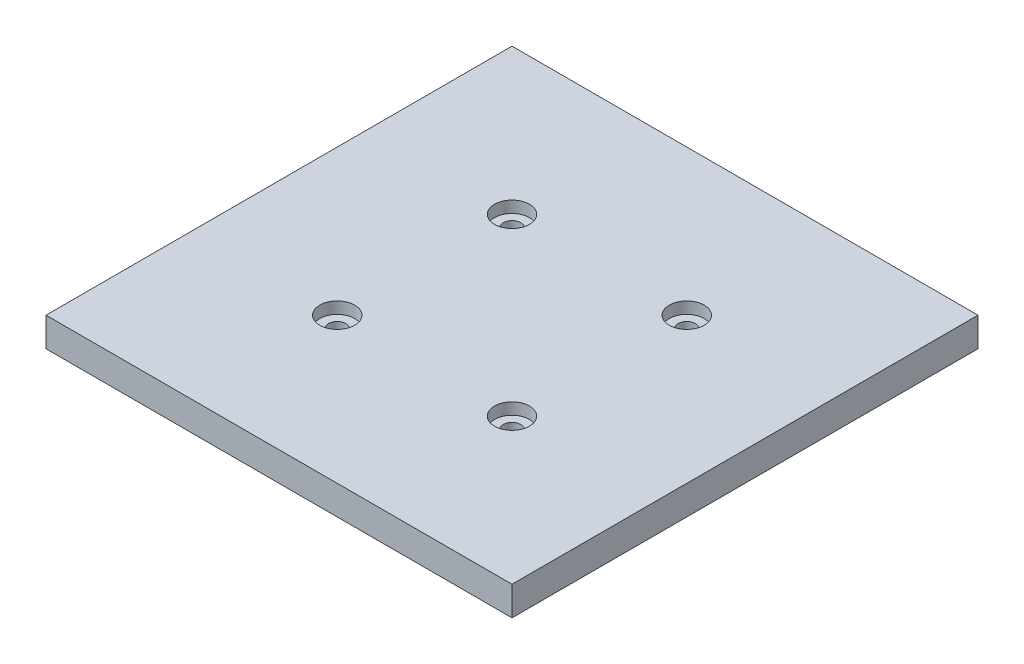
SolidWorks part; units mm, degrees
material "ABS"
ref_plane "Plan de face" through (0, 0, 0) normal (0, 0, 1) x (1, 0, 0)
ref_plane "Plan de dessus" through (0, 0, 0) normal (0, 1, 0) x (1, 0, 0)
ref_plane "Plan de droite" through (0, 0, 0) normal (1, 0, 0) x (0, 0, -1)
sketch "Esquisse1" plane through (0, 0, 0) normal (0, 1, 0) x (1, 0, 0)
  line L0 (0, 0) -> (0, 40) construction
  line L1 (-40, 40) -> (40, 40)
  line L2 (-40, 40) -> (-40, -40)
  line L3 (-40, -40) -> (40, -40)
  line L4 (40, 40) -> (40, -40)
  line L5 (0, 0) -> (40, 0) construction
  circle A0 centre (-15, 15) radius 1.5
  circle A1 centre (15, 15) radius 1.5
  circle A2 centre (-15, -15) radius 1.5
  circle A3 centre (15, -15) radius 1.5
  dimension "D4" = 3
  dimension "D1" = 80
  dimension "D2" = 15
  dimension "D3" = 15
extrude "Extrusion1" add sketch "Esquisse1" along normal blind 5
sketch "Esquisse2" plane through (0, 5, 0) normal (0, 1, 0) x (1, 0, 0)
  line L0 (0, 0) -> (0, 40) construction
  line L1 (40, 40) -> (-40, 40) construction
  line L2 (0, 0) -> (40, 0) construction
  line L3 (40, -40) -> (40, 40) construction
  circle A0 centre (-15, 15) radius 3
  circle A1 centre (15, 15) radius 3
  circle A2 centre (15, -15) radius 3
  circle A3 centre (-15, -15) radius 3
  dimension "D1" = 6
extrude "Enlèv. mat.-Extru.1" cut sketch "Esquisse2" against normal blind 2
